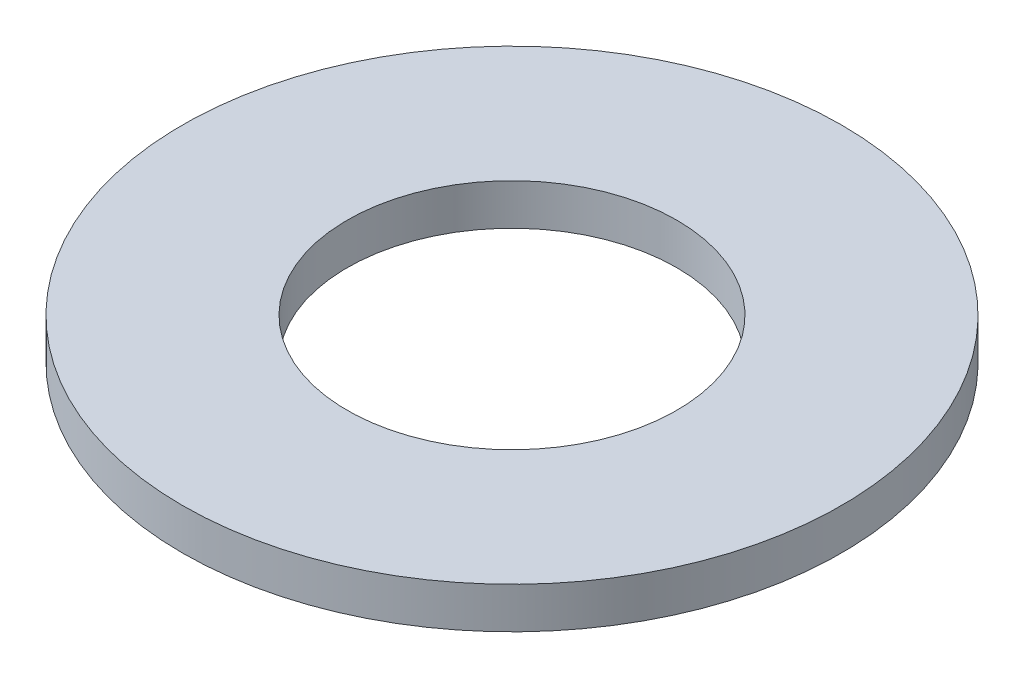
SolidWorks part; units mm, degrees
ref_plane "Front Plane" through (0, 0, 0) normal (0, 0, 1) x (1, 0, 0)
ref_plane "Top Plane" through (0, 0, 0) normal (0, 1, 0) x (1, 0, 0)
ref_plane "Right Plane" through (0, 0, 0) normal (1, 0, 0) x (0, 0, -1)
sketch "Sketch1" plane through (0, 0, 0) normal (0, 0, 1) x (1, 0, 0)
  line L0 (8, 0) -> (16, 0)
  line L1 (16, 0) -> (16, 2)
  line L2 (16, 2) -> (8, 2)
  line L3 (8, 2) -> (8, 0)
  line L4 (0, 0) -> (0, 30.7333) construction
  dimension "D1" = 8
  dimension "D2" = 8
  dimension "D3" = 2
revolve "Revolve1" add sketch "Sketch1" angle 360 about L4
